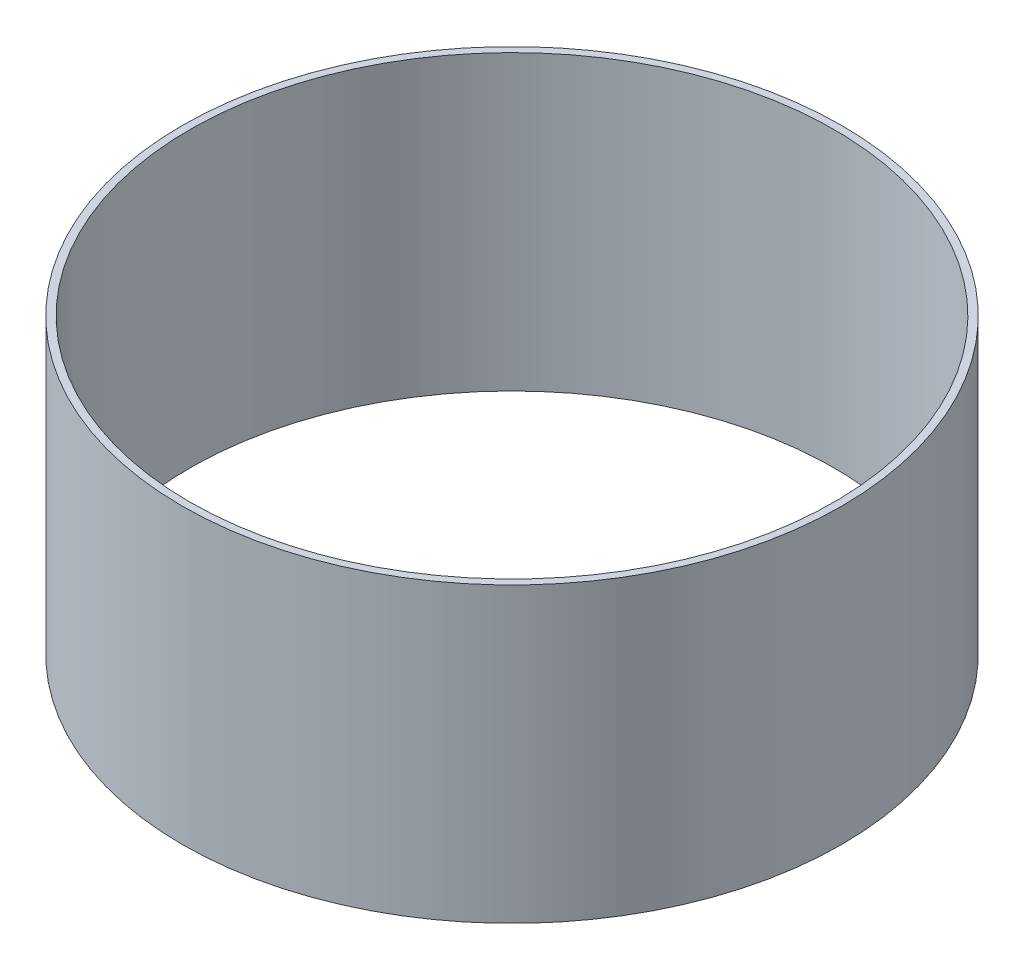
SolidWorks part; units mm, degrees
ref_plane "Front Plane" through (0, 0, 0) normal (0, 0, 1) x (1, 0, 0)
ref_plane "Top Plane" through (0, 0, 0) normal (0, 1, 0) x (1, 0, 0)
ref_plane "Right Plane" through (0, 0, 0) normal (1, 0, 0) x (0, 0, -1)
sketch "Sketch1" plane through (0, 0, 0) normal (0, 1, 0) x (1, 0, 0)
  circle A0 centre (0, 0) radius 22.5
  dimension "D1" = 45
extrude "Boss-Extrude1" add sketch "Sketch1" along normal blind 20
sketch "Sketch2" plane through (0, 20, 0) normal (0, 1, 0) x (1, 0, 0)
  circle A0 centre (0, 0) radius 22
  dimension "D1" = 44
extrude "Cut-Extrude1" cut sketch "Sketch2" against normal blind 20
